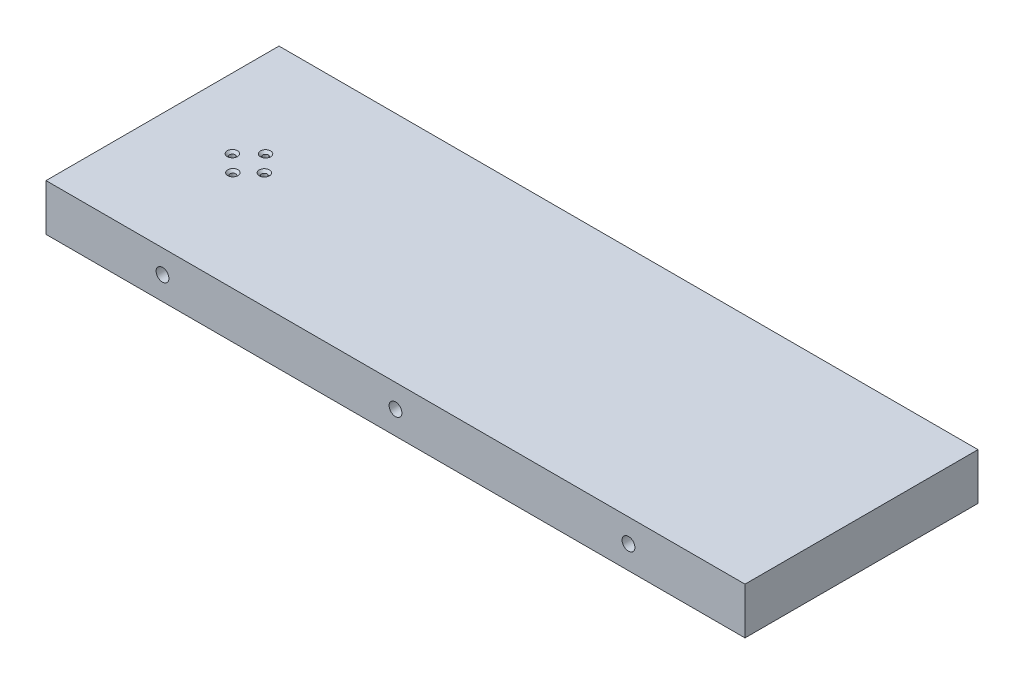
SolidWorks part; units mm, degrees
ref_plane "Front Plane" through (0, 0, 0) normal (0, 0, 1) x (1, 0, 0)
ref_plane "Top Plane" through (0, 0, 0) normal (0, 1, 0) x (1, 0, 0)
ref_plane "Right Plane" through (0, 0, 0) normal (1, 0, 0) x (0, 0, -1)
sketch "Sketch4" plane through (0, 0, 0) normal (0, 1, 0) x (1, 0, 0)
  line L1 (-150, 50) -> (150, 50)
  line L2 (-150, 50) -> (-150, -50)
  line L3 (-150, -50) -> (150, -50)
  line L4 (150, 50) -> (150, -50)
  line L5 (-150, 50) -> (150, -50) construction
  line L6 (-150, -50) -> (150, 50) construction
  point P0 (0, 0)
  dimension "D1" = 300
  dimension "D2" = 100
extrude "Boss-Extrude2" add sketch "Sketch4" along normal blind 20
hole_wizard "CSK for M2 Flat Head Machine Screw1" positions "Sketch7" profile "Sketch8" countersink size "M2" standard "ANSI Metric" end condition through all
sketch "Sketch7" plane through (0, 20, 0) normal (0, 1, 0) x (1, 0, 0)
  line L0 (-150, 50) -> (-150, -50) construction
  line L1 (-150, -50) -> (150, -50) construction
  point P0 (-120, 0)
  point P2 (-106, -0.2738)
  point P4 (-112.8181, 7.0415)
  point P6 (-112.8181, -6.9585)
  dimension "D1" = 10
  dimension "D2" = 14
  dimension "D3" = 14
  dimension "D4" = 10
  dimension "D5" = 30
  dimension "D6" = 50
sketch "Sketch8" plane through (-120, 20, 0) normal (1, 0, 0) x (0, 0, 1)
  line L0 (0, 0) -> (0, 20)
  line L1 (0, 20) -> (1.2, 20)
  line L2 (1.2, 20) -> (1.2, 1)
  line L3 (1.2, 1) -> (2.2, 0)
  line L5 (2.2, 0) -> (0, 0)
  line L6 (-1.2, 1) -> (-2.2, 0) construction
  line L11 (0, -6.35) -> (0, 107.95) construction
  dimension "Thru Hole Dia." = 2.4
  dimension "Thru Hole Depth" = 20
  dimension "Near C'Sink Dia." = 4.4
  dimension "Near C'Sink Angle" = 90
hole_wizard "CBORE for M5 Hex Head Bolt1" positions "Sketch12" profile "Sketch13" counterbore size "M5" standard "ANSI Metric" end condition through all
sketch "Sketch12" plane through (0, 0, -50) normal (0, 0, -1) x (-1, 0, 0)
  line L0 (-150, 20) -> (-150, 0) construction
  line L1 (-150, 20) -> (150, 20) construction
  point P0 (0, 10)
  point P2 (-100, 10)
  point P4 (100, 10)
  dimension "D1" = 100
  dimension "D2" = 100
  dimension "D3" = 50
  dimension "D4" = 10
  dimension "D5" = 10
sketch "Sketch13" plane through (0, 10, -50) normal (1, 0, 0) x (0, 1, 0)
  line L0 (0, 0) -> (0, 100)
  line L1 (0, 100) -> (2.75, 100)
  line L3 (2.75, 100) -> (2.75, 3.58)
  line L4 (2.75, 3.58) -> (6.12, 3.58)
  line L5 (6.12, 3.58) -> (6.12, 0)
  line L7 (6.12, 0) -> (0, 0)
  line L11 (0, -6.35) -> (0, 107.95) construction
  dimension "Thru Hole Dia." = 5.5
  dimension "Thru Hole Depth" = 100
  dimension "C'Bore Dia." = 12.24
  dimension "C'Bore Depth" = 3.58
